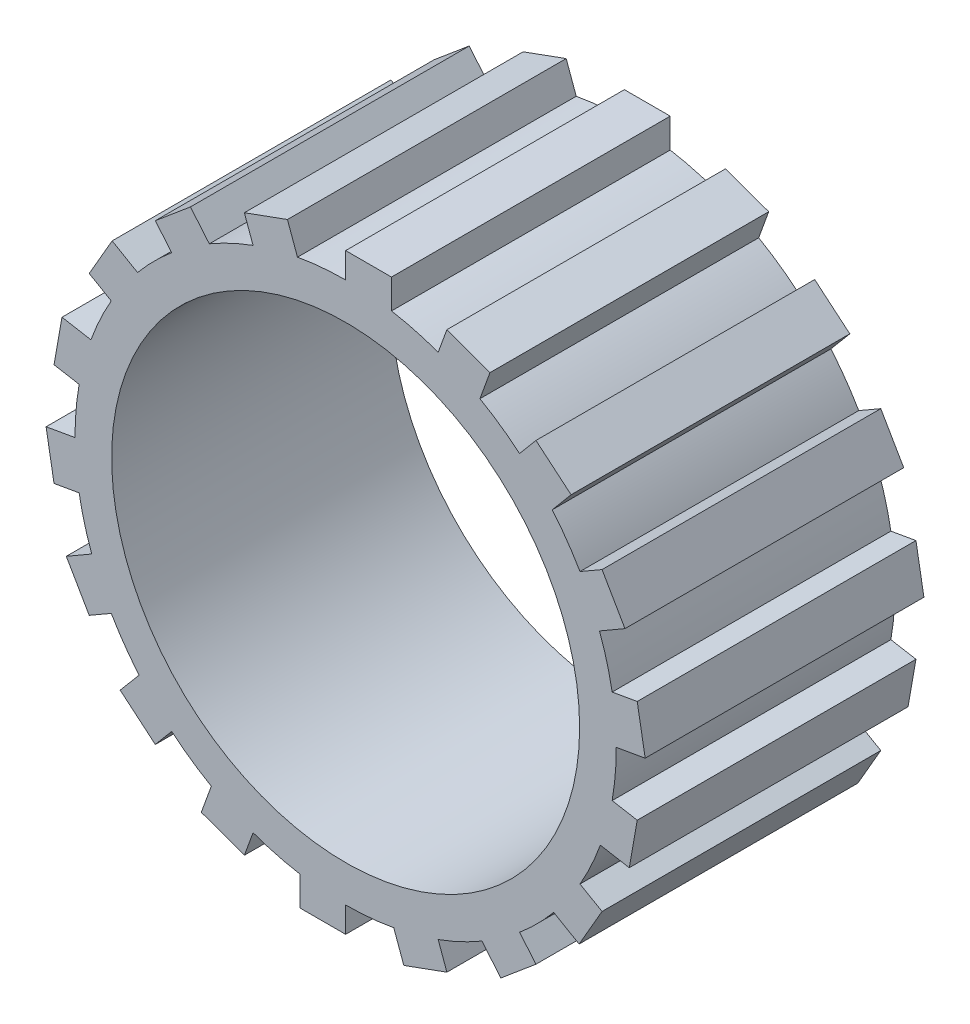
SolidWorks part; units mm, degrees
ref_plane "Front Plane" through (0, 0, 0) normal (0, 0, 1) x (1, 0, 0)
ref_plane "Top Plane" through (0, 0, 0) normal (0, 1, 0) x (1, 0, 0)
ref_plane "Right Plane" through (0, 0, 0) normal (1, 0, 0) x (0, 0, -1)
sketch "Sketch1" plane through (0, 0, 0) normal (0, 0, 1) x (1, 0, 0)
  circle A0 centre (0, 0) radius 7.35
  circle A1 centre (0, 0) radius 8.5
  dimension "D1" = 14.7
  dimension "D2" = 17
extrude "Boss-Extrude3" add sketch "Sketch1" along normal blind 17.51
ref_plane "Plane1" through (0, 8.5, 0) normal (0, 1, 0) x (1, 0, 0)
sketch "Sketch3" plane through (0, 8.5, 0) normal (0, 1, 0) x (1, 0, 0)
  line L0 (0, -17.51) -> (0, 0) construction
  line L1 (-8.5, -17.51) -> (8.5, -17.51) construction
  line L3 (0, -8.755) -> (1.4399, -8.755)
  line L4 (0, -8.755) -> (0, -17.51)
  line L5 (0, -17.51) -> (1.4399, -17.51)
  line L6 (1.4399, -8.755) -> (1.4399, -17.51)
extrude "Boss-Extrude5" add sketch "Sketch3" against normal blind 0.3 and the other way blind 0.8
pattern_circular "CirPattern1" count 18 over 360 about axis through (0, 0, 0) along (0, 0, 1) of "Boss-Extrude5"
sketch "Sketch6" plane through (0, 0, 0) normal (0, 0, -1) x (-1, 0, 0)
  circle A0 centre (0, 0) radius 8.5
extrude "Cut-Extrude1" cut sketch "Sketch6" against normal up to surface (8.755 mm away) up to face at (-7.3274, 5.0626, 8.755)
